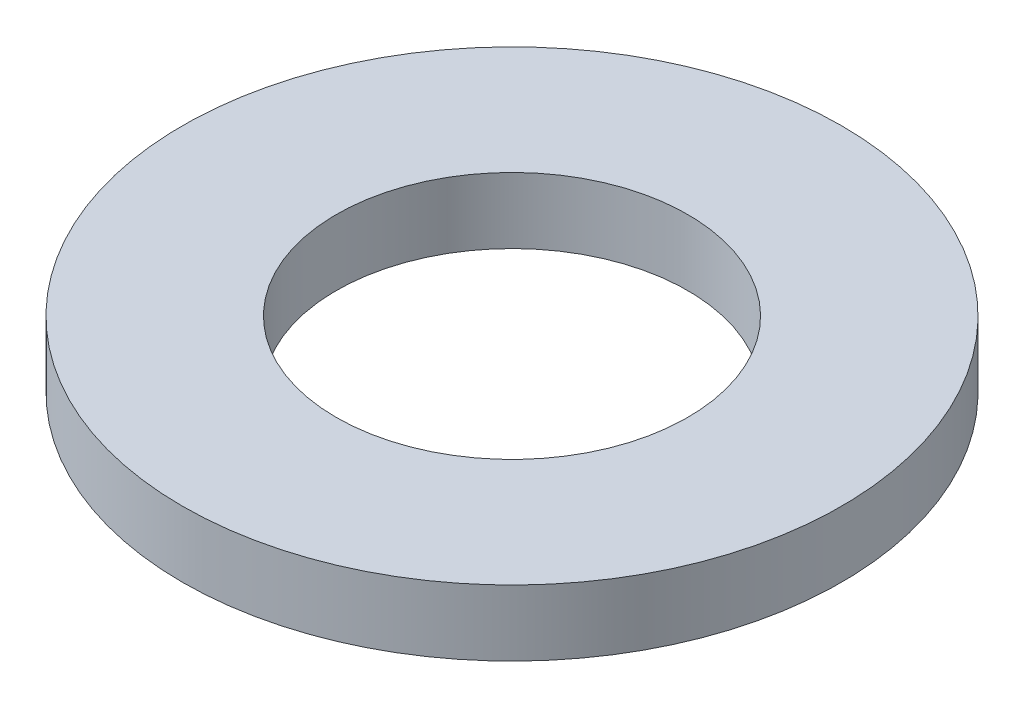
SolidWorks part; units mm, degrees
ref_plane "Ön Düzlem" through (0, 0, 0) normal (0, 0, 1) x (1, 0, 0)
ref_plane "Üst Düzlem" through (0, 0, 0) normal (0, 1, 0) x (1, 0, 0)
ref_plane "Sağ Düzlem" through (0, 0, 0) normal (1, 0, 0) x (0, 0, -1)
sketch "Çizim1" plane through (0, 0, 0) normal (0, 1, 0) x (1, 0, 0)
  circle A0 centre (0, 0) radius 7.5
  circle A1 centre (0, 0) radius 4
  dimension "D1" = 8
  dimension "D2" = 15
extrude "Yükseklik-Ekstrüzyon1" add sketch "Çizim1" along normal blind 1.5
